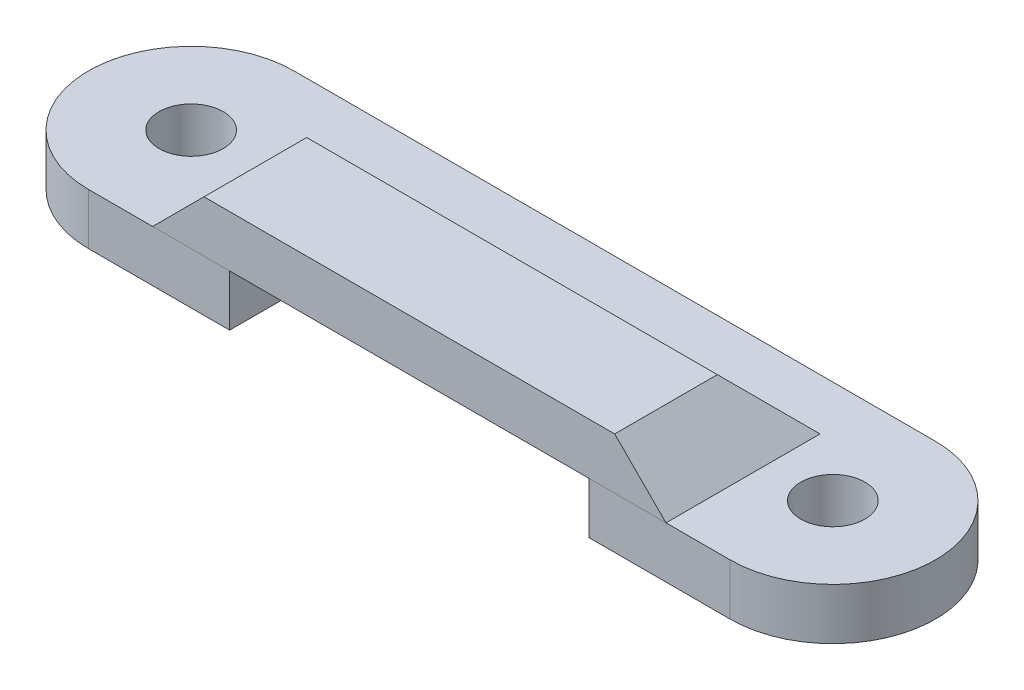
SolidWorks part; units mm, degrees
ref_plane "前视基准面" through (0, 0, 0) normal (0, 0, 1) x (1, 0, 0)
ref_plane "上视基准面" through (0, 0, 0) normal (0, 1, 0) x (1, 0, 0)
ref_plane "右视基准面" through (0, 0, 0) normal (1, 0, 0) x (0, 0, -1)
sketch "草图1" plane through (0, 0, 0) normal (0, 1, 0) x (1, 0, 0)
  line L0 (-25, 9.2974) -> (25, 9.2974)
  line L1 (-25, -6.7026) -> (25, -6.7026)
  arc A0 (-25, -6.7026) -> (-25, 9.2974) centre (-25, 1.2974) cw
  arc A1 (25, 9.2974) -> (25, -6.7026) centre (25, 1.2974) cw
  circle A2 centre (-25, 1.2974) radius 2.5
  circle A3 centre (25, 1.2974) radius 2.5
  dimension "D1" = 5
  dimension "D2" = 5
  dimension "D5" = 8
  dimension "D3" = 50
  dimension "D4" = 25
extrude "凸台-拉伸1" add sketch "草图1" along normal blind 4
sketch "草图2" plane through (0, 0, 6.7026) normal (0, 0, 1) x (1, 0, 0)
  line L0 (-20, 4) -> (-16, 8)
  line L1 (-25, 4) -> (25, 4) construction
  line L2 (-16, 8) -> (16, 8)
  line L3 (16, 8) -> (20, 4)
  line L4 (20, 4) -> (-20, 4)
  dimension "D1" = 4
  dimension "D2" = 20
  dimension "D3" = 40
  dimension "D4" = 45
  dimension "D5" = 45
extrude "凸台-拉伸2" add sketch "草图2" against normal blind 12 separate body
sketch "草图3" plane through (0, 0, 6.7026) normal (0, 0, 1) x (1, 0, 0)
  line L0 (-25, 0) -> (25, 0) construction
  line L1 (-14, 0) -> (14, 0)
  line L2 (-14, 0) -> (-14, 4)
  line L3 (-14, 4) -> (14, 4)
  line L4 (14, 0) -> (14, 4)
  line L5 (-20, 4) -> (20, 4) construction
  dimension "D1" = 28
  dimension "D2" = 14
extrude "切除-拉伸1" cut sketch "草图3" against normal blind 8
sketch "草图4" plane through (0, 0, 0) normal (1, 0, 0) x (0, 0, -1)
  line L0 (5.2974, 8) -> (1.2974, 8)
  line L1 (5.2974, 8) -> (-6.7026, 8) construction
  line L2 (1.2974, 8) -> (5.2974, 4)
  line L3 (5.2974, 4) -> (5.2974, 8)
  dimension "D1" = 4
extrude "切除-拉伸2" cut sketch "草图4" against normal through all both and the other way through all
